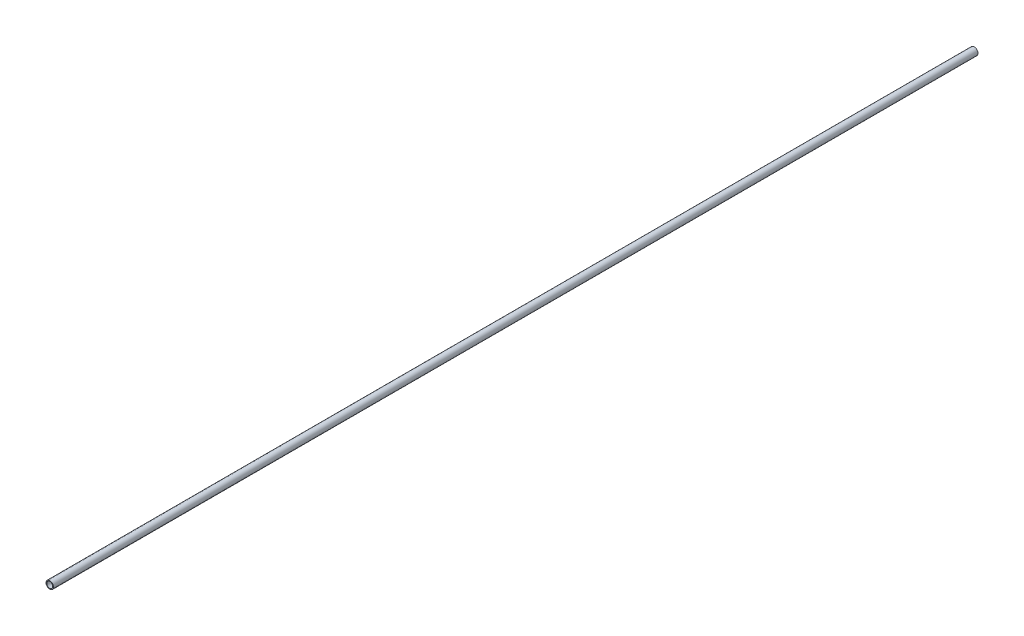
SolidWorks part; units mm, degrees
material "Thornel Mat VMA"
ref_plane "前视基准面" through (0, 0, 0) normal (0, 0, 1) x (1, 0, 0)
ref_plane "上视基准面" through (0, 0, 0) normal (0, 1, 0) x (1, 0, 0)
ref_plane "右视基准面" through (0, 0, 0) normal (1, 0, 0) x (0, 0, -1)
other "Configuration Table"
sketch "草图1" plane through (0, 0, 0) normal (0, 0, 1) x (1, 0, 0)
  circle A0 centre (0, 0) radius 5
  circle A1 centre (0, 0) radius 4
  dimension "D1" = 10
  dimension "D2" = 8
extrude "凸台-拉伸1" add sketch "草图1" along normal blind 1230
